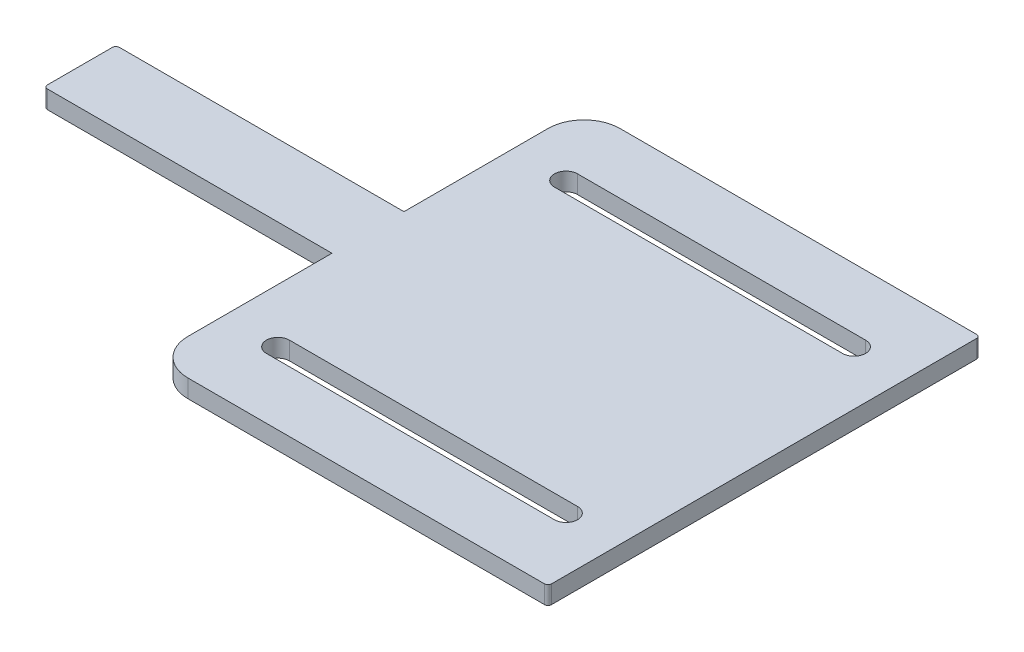
SolidWorks part; units mm, degrees
ref_plane "Front Plane" through (0, 0, 0) normal (0, 0, 1) x (1, 0, 0)
ref_plane "Top Plane" through (0, 0, 0) normal (0, 1, 0) x (1, 0, 0)
ref_plane "Right Plane" through (0, 0, 0) normal (1, 0, 0) x (0, 0, -1)
sketch "Sketch1" plane through (0, 0, 0) normal (0, 1, 0) x (1, 0, 0)
  line L0 (0, 0) -> (28.3099, 0) construction
  line L1 (-69.85, -76.2) -> (69.85, -76.2)
  line L2 (-69.85, -76.2) -> (-69.85, 76.2)
  line L3 (-69.85, 76.2) -> (69.85, 76.2)
  line L4 (69.85, -76.2) -> (69.85, 76.2)
  line L5 (-69.85, -76.2) -> (69.85, 76.2) construction
  line L6 (-69.85, 76.2) -> (69.85, -76.2) construction
  line L7 (-50.8, 54.864) -> (50.8, 54.864)
  line L8 (-50.8, 54.864) -> (-50.8, 46.736)
  line L9 (-50.8, 46.736) -> (50.8, 46.736)
  line L10 (50.8, 54.864) -> (50.8, 46.736)
  line L11 (-50.8, 54.864) -> (50.8, 46.736) construction
  line L12 (-50.8, 46.736) -> (50.8, 54.864) construction
  line L13 (-50.8, -46.736) -> (50.8, -54.864) construction
  line L14 (-50.8, -54.864) -> (50.8, -46.736) construction
  line L15 (50.8, -54.864) -> (50.8, -46.736)
  line L16 (-50.8, -46.736) -> (50.8, -46.736)
  line L17 (-50.8, -54.864) -> (-50.8, -46.736)
  line L18 (-50.8, -54.864) -> (50.8, -54.864)
  circle A0 centre (50.8, 50.8) radius 4.064
  circle A1 centre (-50.8, 50.8) radius 4.064
  circle A2 centre (-50.8, -50.8) radius 4.064
  circle A3 centre (50.8, -50.8) radius 4.064
  point P0 (0, 0)
  point P5 (0, 50.8)
  point P25 (0, -50.8)
  dimension "D3" = 101.6
  dimension "D1" = 139.7
  dimension "D2" = 152.4
  dimension "D4" = 101.6
  dimension "D5" = 8.128
extrude "Boss-Extrude1" add sketch "Sketch1" along normal blind 6.35 contours L1 L4 L3 L2 A1 L7 A0 L9 L16 A3 L18 A2
fillet "Fillet1" radius 12.7 2 edges at (-69.85, 3.175, -76.2) (-69.85, 3.175, 76.2)
sketch "Sketch2" plane through (0, 6.35, 0) normal (0, 1, 0) x (1, 0, 0)
  line L0 (-69.85, -63.5) -> (-69.85, 63.5) construction
  line L1 (-171.45, 12.7) -> (-69.85, 12.7)
  line L2 (-171.45, 12.7) -> (-171.45, -12.7)
  line L3 (-171.45, -12.7) -> (-69.85, -12.7)
  line L4 (-69.85, 12.7) -> (-69.85, -12.7)
  line L5 (-171.45, 12.7) -> (-69.85, -12.7) construction
  line L6 (-171.45, -12.7) -> (-69.85, 12.7) construction
  point P0 (-120.65, 0)
  point P7 (0, 0)
  dimension "D1" = 25.4
  dimension "D2" = 101.6
extrude "Boss-Extrude2" add sketch "Sketch2" against normal up to surface (6.35 mm away) up to face at (0, 0, -50.8)
fillet "Fillet2" radius 1.27 4 edges at (69.85, 3.175, 76.2) (69.85, 3.175, -76.2) (-171.45, 3.175, -12.7) (-171.45, 3.175, 12.7)
